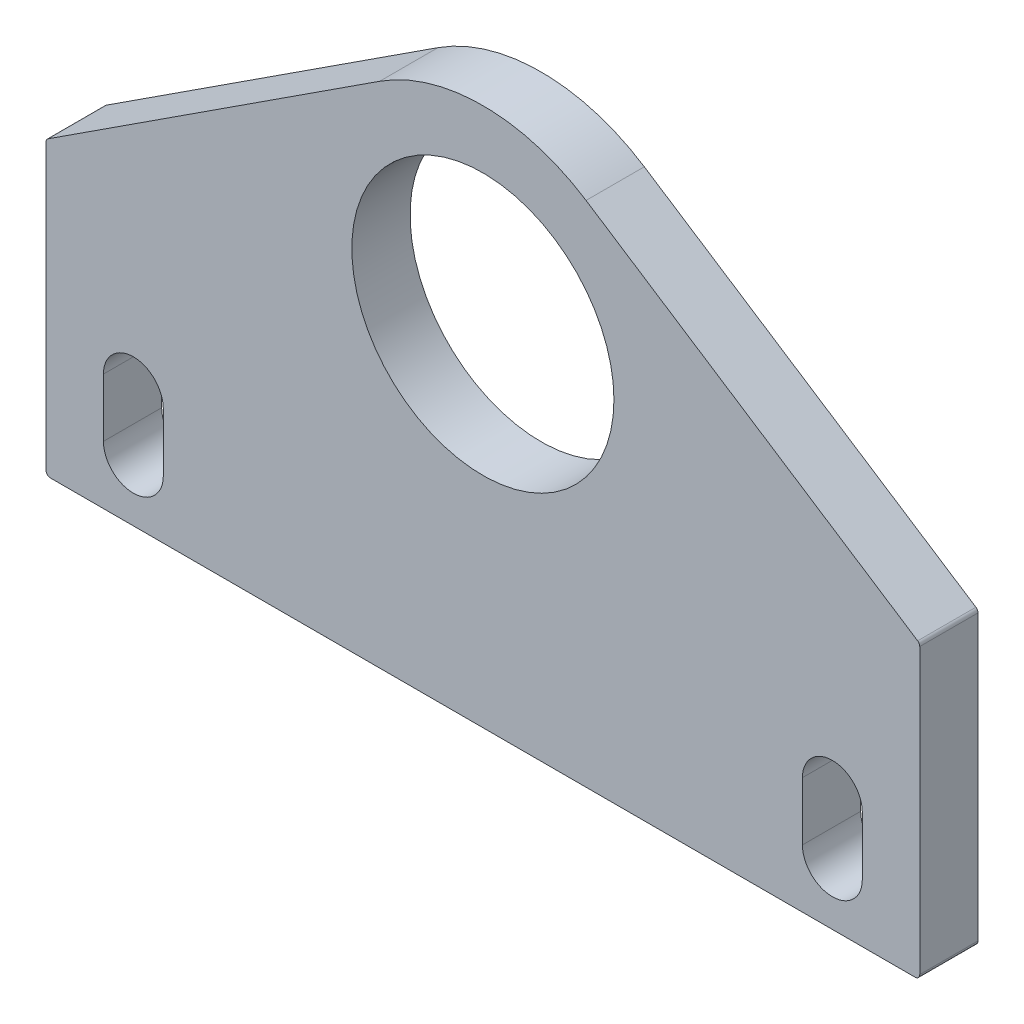
SolidWorks part; units mm, degrees
material "6061-T6 (SS)"
ref_plane "Front Plane" through (0, 0, 0) normal (0, 0, 1) x (1, 0, 0)
ref_plane "Top Plane" through (0, 0, 0) normal (0, 1, 0) x (1, 0, 0)
ref_plane "Right Plane" through (0, 0, 0) normal (1, 0, 0) x (0, 0, -1)
sketch "Sketch1" plane through (0, 0, 0) normal (0, 0, 1) x (1, 0, 0)
  line L0 (-11.2498, 17.3017) -> (-47.625, -6.35)
  line L1 (-47.625, -6.35) -> (-47.625, -38.1)
  line L2 (-47.625, -38.1) -> (47.625, -38.1)
  line L3 (47.625, -38.1) -> (47.625, -6.35)
  line L4 (47.625, -6.35) -> (11.2498, 17.3017)
  line L5 (-38.1, -25.4) -> (-38.1, -31.75) construction
  line L6 (-34.8361, -25.4) -> (-34.8361, -31.75)
  line L7 (-41.3639, -25.4) -> (-41.3639, -31.75)
  line L8 (38.1, -25.4) -> (38.1, -31.75) construction
  line L9 (41.3639, -25.4) -> (41.3639, -31.75)
  line L10 (34.8361, -25.4) -> (34.8361, -31.75)
  line L11 (-38.1, -28.575) -> (0, 0) construction
  line L12 (0, 0) -> (38.1, -28.575) construction
  circle A0 centre (0, 0) radius 14.2875
  arc A1 (11.2498, 17.3017) -> (-11.2498, 17.3017) centre (0, 0) ccw
  arc A2 (-34.8361, -25.4) -> (-41.3639, -25.4) centre (-38.1, -25.4) ccw
  arc A3 (-41.3639, -31.75) -> (-34.8361, -31.75) centre (-38.1, -31.75) ccw
  arc A4 (41.3639, -25.4) -> (34.8361, -25.4) centre (38.1, -25.4) ccw
  arc A5 (34.8361, -31.75) -> (41.3639, -31.75) centre (38.1, -31.75) ccw
  point P10 (-38.1, -28.575)
  point P17 (38.1, -28.575)
  dimension "D1" = 28.575
  dimension "D4" = 6.35
  dimension "D2" = 95.25
  dimension "D3" = 38.1
  dimension "D5" = 31.75
  dimension "D6" = 76.2
  dimension "D7" = 6.5278
  dimension "D8" = 6.35
  dimension "D9" = 6.35
extrude "Boss-Extrude1" add sketch "Sketch1" along normal blind 6.35
fillet "Fillet1" radius 0.508 4 edges at (-47.625, -38.1, 3.175) (-47.625, -6.35, 3.175) (47.625, -38.1, 3.175) (47.625, -6.35, 3.175)
